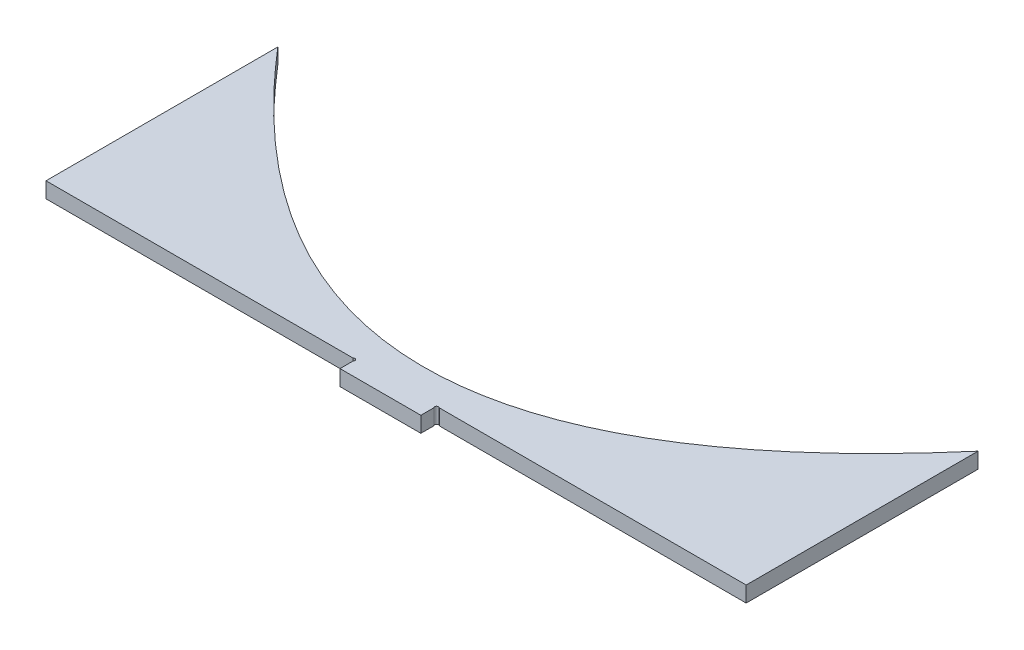
SolidWorks part; units mm, degrees
ref_plane "Alzado" through (0, 0, 0) normal (0, 0, 1) x (1, 0, 0)
ref_plane "Planta" through (0, 0, 0) normal (0, 1, 0) x (1, 0, 0)
ref_plane "Vista lateral" through (0, 0, 0) normal (1, 0, 0) x (0, 0, -1)
sketch "Croquis1" plane through (0, 0, 0) normal (0, 1, 0) x (1, 0, 0)
  line L0 (-237.4382, 168.6502) -> (-237.4382, -9.1064)
  line L1 (-237.4382, -9.1064) -> (-2.1213, -9.1064)
  line L2 (299.4382, -9.1064) -> (299.4382, 168.6502)
  line L4 (31, -21.1064) -> (0, -21.1064)
  line L5 (0, -11.2277) -> (0, -21.1064)
  line L6 (31, -21.1064) -> (62, -21.1064)
  line L7 (62, -21.1064) -> (62, -11.2277)
  line L9 (64.1213, -9.1064) -> (299.4382, -9.1064)
  arc A0 (0, -11.2277) -> (-2.1213, -9.1064) centre (-1.0607, -10.167) ccw
  arc A1 (64.1213, -9.1064) -> (62, -11.2277) centre (63.0607, -10.167) ccw
  parabola Q0 (31, 12) -> (-237.4382, 168.6502) focus (31, 127) apex (31, 12)
  parabola Q1 (299.4382, 168.6502) -> (31, 12) focus (31, 127) apex (31, 12)
  dimension "D1" = 177.7565
  dimension "D2" = 536.8764
extrude "Saliente-Extruir1" add sketch "Croquis1" along normal blind 12
